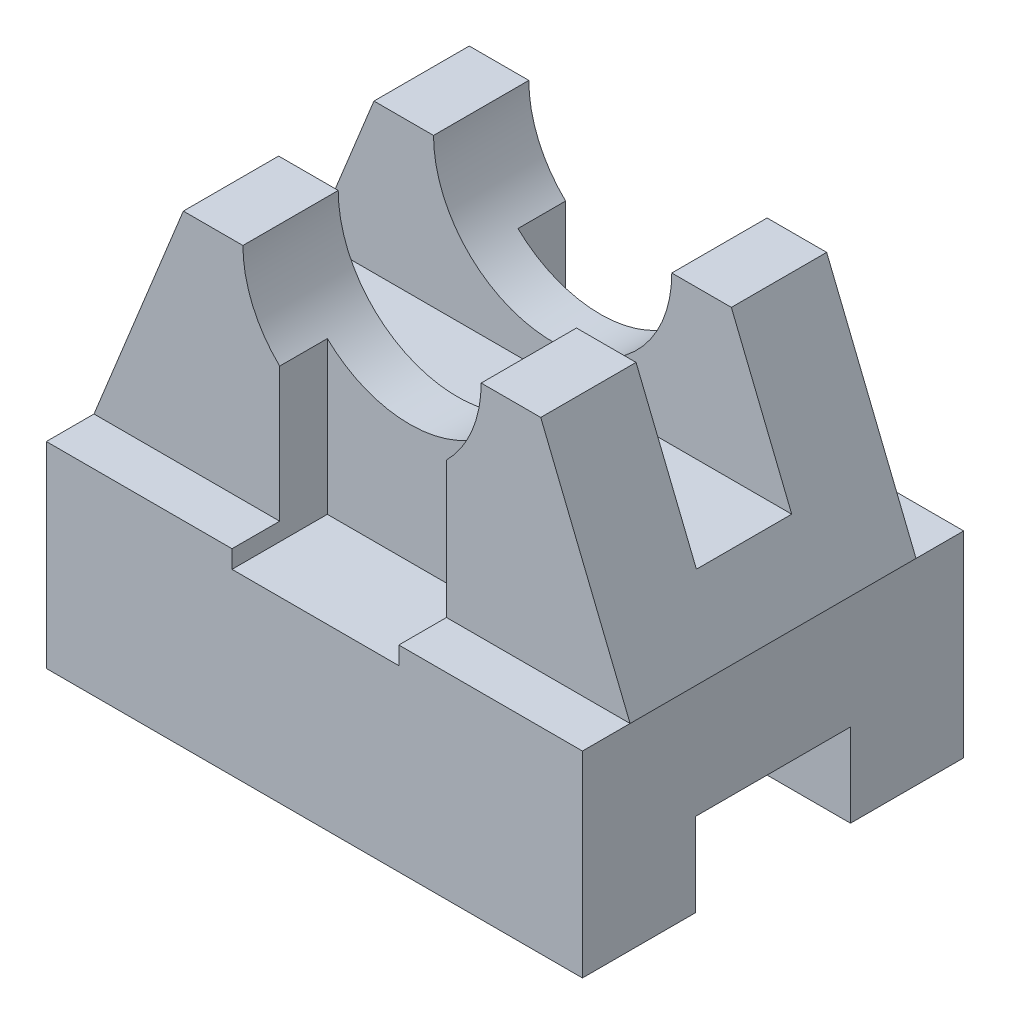
SolidWorks part; units mm, degrees
ref_plane "Front Plane" through (0, 0, 0) normal (0, 0, 1) x (1, 0, 0)
ref_plane "Top Plane" through (0, 0, 0) normal (0, 1, 0) x (1, 0, 0)
ref_plane "Right Plane" through (0, 0, 0) normal (1, 0, 0) x (0, 0, -1)
sketch "Sketch1" plane through (0, 0, 0) normal (0, 1, 0) x (1, 0, 0)
  line L1 (-45, 32) -> (45, 32)
  line L2 (-45, 32) -> (-45, -32)
  line L3 (-45, -32) -> (45, -32)
  line L4 (45, 32) -> (45, -32)
  line L5 (-45, 32) -> (45, -32) construction
  line L6 (-45, -32) -> (45, 32) construction
  point P0 (0, 0)
  dimension "D1" = 64
  dimension "D2" = 90
extrude "Boss-Extrude1" add sketch "Sketch1" along normal blind 33
sketch "Sketch2" plane through (45, 0, 0) normal (1, 0, 0) x (0, 0, -1)
  line L0 (13, 0) -> (13, 14)
  line L1 (13, 0) -> (-13, 0)
  line L2 (13, 14) -> (-13, 14)
  line L3 (-13, 0) -> (-13, 14)
  line L4 (-32, 0) -> (32, 0) construction
  dimension "D1" = 14
  dimension "D2" = 26
extrude "Cut-Extrude1" cut sketch "Sketch2" against normal through all
sketch "Sketch3" plane through (0, 0, 0) normal (0, 0, 1) x (1, 0, 0)
  line L0 (0, 0) -> (0, 70) construction
  line L1 (0, 70) -> (30, 70)
  line L2 (30, 70) -> (-30, 70)
  line L3 (30, 70) -> (45, 33)
  line L4 (45, 33) -> (0, 33)
  line L5 (0, 33) -> (0, 70)
  circle A0 centre (0, 70) radius 20
  dimension "D1" = 70
extrude "Boss-Extrude2" add sketch "Sketch3" along normal mid plane 48 contours A0 L5 L4 L3 L2
mirror "Mirror2" about plane through (0, 0, 0) normal (1, 0, 0) of "Boss-Extrude2"
sketch "Sketch4" plane through (0, 70, 0) normal (0, 1, 0) x (1, 0, 0)
  line L1 (43.4465, -8) -> (-43.4465, -8)
  line L2 (43.4465, -8) -> (43.4465, 8)
  line L3 (43.4465, 8) -> (-43.4465, 8)
  line L4 (-43.4465, -8) -> (-43.4465, 8)
  line L5 (43.4465, -8) -> (-43.4465, 8) construction
  line L6 (43.4465, 8) -> (-43.4465, -8) construction
  point P0 (0, 0)
  dimension "D1" = 16
extrude "Cut-Extrude2" cut sketch "Sketch4" against normal blind 25
sketch "Sketch5" plane through (0, 70, 0) normal (0, 1, 0) x (1, 0, 0)
  line L1 (45, -32) -> (-45, -32) construction
  line L2 (45, -32) -> (45, 32) construction
  line L3 (45, 32) -> (-45, 32) construction
  line L4 (-45, -32) -> (-45, 32) construction
  line L5 (45, -32) -> (-45, 32) construction
  line L6 (45, 32) -> (-45, -32) construction
  point P0 (0, 0)
  dimension "D1" = 64
  dimension "D2" = 90
ref_plane "Plane1" through (0, 70, 0) normal (0, 1, 0) x (1, 0, 0)
sketch "Sketch6" plane through (0, 70, 0) normal (0, 1, 0) x (1, 0, 0)
  line L1 (-13.8263, -32) -> (14.1737, -32)
  line L2 (-13.8263, -32) -> (-13.8263, -16)
  line L3 (-13.8263, -16) -> (14.1737, -16)
  line L4 (14.1737, -32) -> (14.1737, -16)
  line L5 (-45, -32) -> (45, -32) construction
  dimension "D1" = 16
  dimension "D2" = 28
extrude "Cut-Extrude3" cut sketch "Sketch6" against normal blind 40
mirror "Mirror3" about plane through (0, 0, 0) normal (0, 0, 1) of "Cut-Extrude3"
